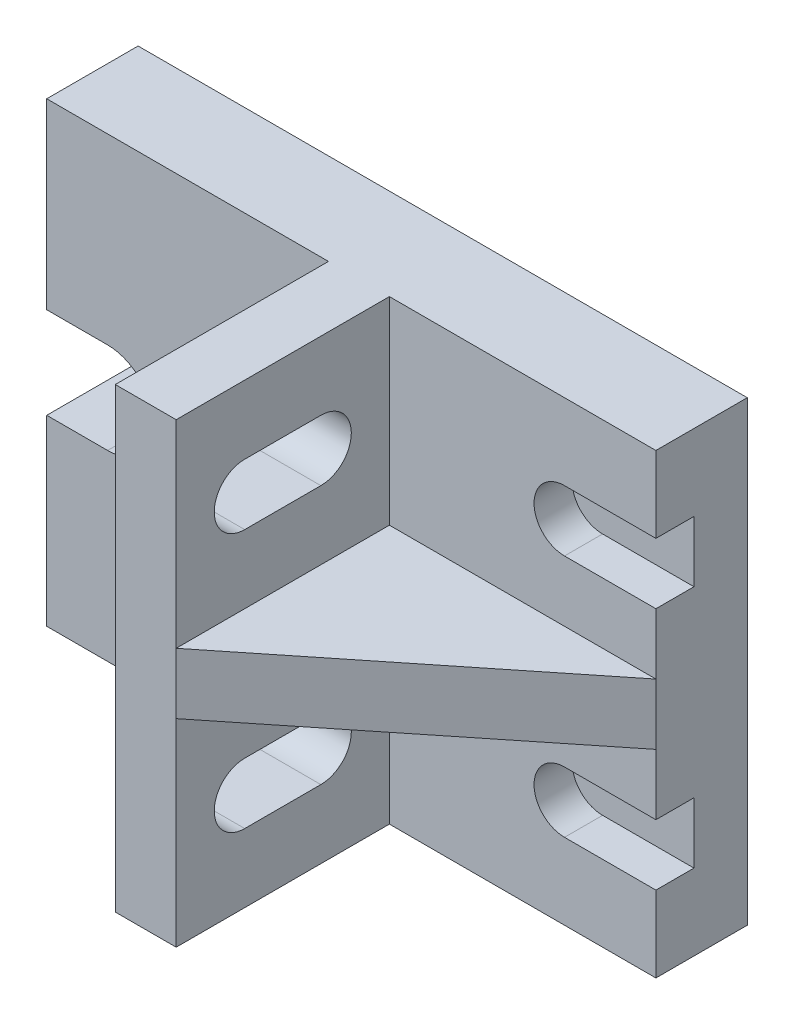
SolidWorks part; units mm, degrees
ref_plane "Спереди" through (0, 0, 0) normal (0, 0, 1) x (1, 0, 0)
ref_plane "Сверху" through (0, 0, 0) normal (0, 1, 0) x (1, 0, 0)
ref_plane "Справа" through (0, 0, 0) normal (1, 0, 0) x (0, 0, -1)
sketch "Эскиз1" plane through (0, 0, 0) normal (0, 0, 1) x (1, 0, 0)
  line L1 (0, 0) -> (200, 0)
  line L2 (0, 0) -> (0, -150)
  line L3 (0, -150) -> (200, -150)
  line L4 (200, 0) -> (200, -150)
  point P4 (0, 0)
  dimension "D1" = 200
  dimension "D2" = 150
extrude "Бобышка-Вытянуть1" add sketch "Эскиз1" along normal blind 30
sketch "Эскиз2" plane through (0, 0, 30) normal (0, 0, 1) x (1, 0, 0)
  line L6 (200, -105) -> (170, -105)
  line L7 (200, -150) -> (200, 0) construction
  line L8 (200, -125) -> (170, -125)
  line L10 (0, 0) -> (0, -150) construction
  line L12 (0, -75) -> (200, -75) construction
  line L13 (200, -25) -> (170, -25)
  line L14 (200, -45) -> (170, -45)
  line L16 (200, -25) -> (200, -45)
  line L17 (200, -105) -> (200, -125)
  arc A0 (170, -125) -> (170, -105) centre (170, -115) cw
  arc A2 (170, -25) -> (170, -45) centre (170, -35) ccw
  point P33 (0, 0)
  dimension "D5" = 25
  dimension "D6" = 20
  dimension "D7" = 30
extrude "Вырез-Вытянуть7" cut sketch "Эскиз2" against normal blind 12.5
sketch "Эскиз5" plane through (0, 0, 30) normal (0, 0, 1) x (1, 0, 0)
  line L0 (0, -60) -> (20, -60)
  line L1 (0, 0) -> (0, -150) construction
  line L2 (0, -90) -> (20, -90)
  line L3 (0, -60) -> (0, -90)
  arc A0 (20, -60) -> (20, -90) centre (20, -75) cw
  dimension "D4" = 15
  dimension "D1" = 30
  dimension "D2" = 20
  dimension "D3" = 20
  dimension "D5" = 60
extrude "Вырез-Вытянуть8" cut sketch "Эскиз5" against normal through all contours L3 L2 A0 L0
sketch "Эскиз6" plane through (0, 0, 30) normal (0, 0, 1) x (1, 0, 0)
  line L0 (200, 0) -> (0, 0) construction
  line L1 (92.5, 0) -> (112.5, 0)
  line L2 (92.5, 0) -> (92.5, -150)
  line L3 (92.5, -150) -> (112.5, -150)
  line L4 (112.5, 0) -> (112.5, -150)
  line L5 (0, -150) -> (200, -150) construction
  dimension "D1" = 92.5
  dimension "D2" = 87.5
extrude "Бобышка-Вытянуть2" add sketch "Эскиз6" along normal blind 70 contours L2 L1 L4 L3
sketch "Эскиз7" plane through (0, -150, 0) normal (0, -1, 0) x (1, 0, 0)
  line L0 (112.5, 100) -> (200, 30)
  line L1 (200, 30) -> (112.5, 30)
  line L2 (112.5, 30) -> (112.5, 100)
extrude "Бобышка-Вытянуть4" add sketch "Эскиз7" along normal blind 20 from offset 85 contours L2 L0 L1 offset against normal yes
sketch "Эскиз10" plane through (112.5, 0, 0) normal (1, 0, 0) x (0, 0, -1)
  line L0 (-100, -117.5) -> (-30, -117.5) construction
  line L1 (-100, -85) -> (-100, -150) construction
  line L2 (-30, -85) -> (-30, -150) construction
  line L3 (-65, -85) -> (-65, -150) construction
  line L4 (-30, -85) -> (-100, -85) construction
  line L5 (-100, -150) -> (-30, -150) construction
  line L6 (-52.5, -117.5) -> (-77.5, -117.5) construction
  line L7 (-52.5, -127.5) -> (-77.5, -127.5)
  line L8 (-52.5, -107.5) -> (-77.5, -107.5)
  line L9 (-100, -75) -> (-30, -75) construction
  line L10 (-100, -85) -> (-100, -65) construction
  line L11 (-30, -85) -> (-30, -65) construction
  line L12 (-52.5, -32.5) -> (-77.5, -32.5) construction
  line L13 (-52.5, -22.5) -> (-77.5, -22.5)
  line L14 (-52.5, -42.5) -> (-77.5, -42.5)
  arc A0 (-52.5, -127.5) -> (-52.5, -107.5) centre (-52.5, -117.5) ccw
  arc A1 (-77.5, -107.5) -> (-77.5, -127.5) centre (-77.5, -117.5) ccw
  arc A2 (-52.5, -22.5) -> (-52.5, -42.5) centre (-52.5, -32.5) cw
  arc A3 (-77.5, -42.5) -> (-77.5, -22.5) centre (-77.5, -32.5) cw
  point P14 (-65, -117.5)
  point P27 (-65, -32.5)
  dimension "D2" = 10
  dimension "D1" = 25
extrude "Вырез-Вытянуть9" cut sketch "Эскиз10" against normal up to surface (20 mm away) up to face at (92.5, -75, 65)
